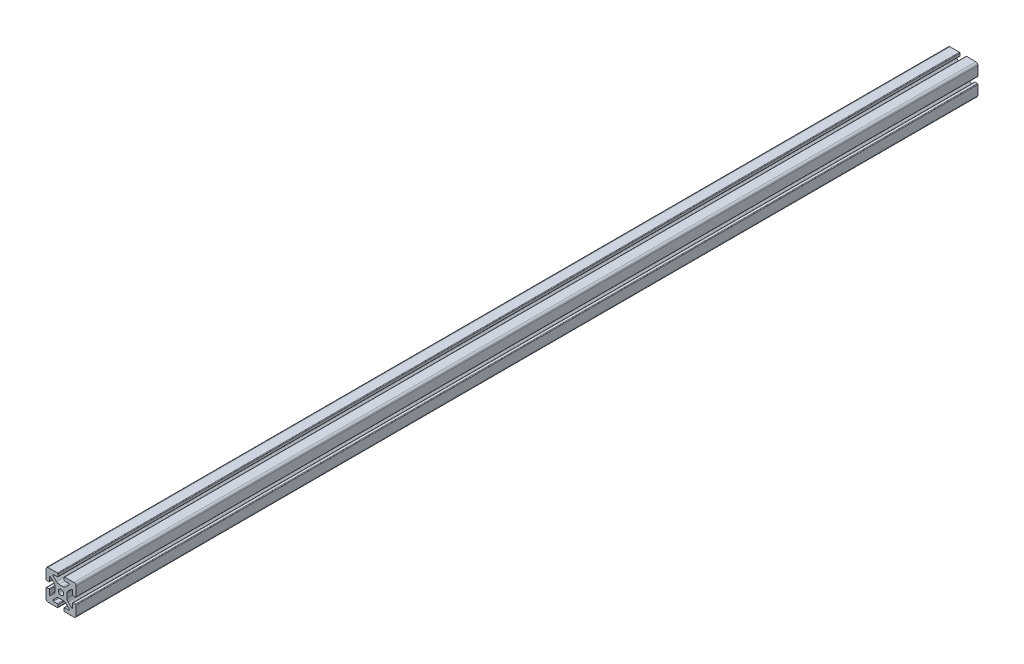
SolidWorks part; units mm, degrees
material "1060 Alloy"
ref_plane "Front Plane" through (0, 0, 0) normal (0, 0, 1) x (1, 0, 0)
ref_plane "Top Plane" through (0, 0, 0) normal (0, 1, 0) x (1, 0, 0)
ref_plane "Right Plane" through (0, 0, 0) normal (1, 0, 0) x (0, 0, -1)
sketch "Sketch1" plane through (0, 0, 0) normal (0, 0, 1) x (1, 0, 0)
  line L72 (4.8, -20) -> (17.2, -20)
  line L73 (20, -17.2) -> (20, -4.8)
  line L74 (19.2, -4) -> (16.1907, -4)
  line L75 (15.3907, -4.8) -> (15.3907, -10.2)
  line L76 (14.025, -10.7657) -> (9.4059, -6.1466)
  line L77 (8, -2.7525) -> (8, 2.7525)
  line L78 (9.4059, 6.1466) -> (14.025, 10.7657)
  line L79 (15.3907, 10.2) -> (15.3907, 4.8)
  line L80 (16.1907, 4) -> (19.2, 4)
  line L81 (20, 4.8) -> (20, 17.2)
  line L82 (17.2, 20) -> (4.8, 20)
  line L83 (4, 19.2) -> (4, 16.1907)
  line L84 (4.8, 15.3907) -> (10.2, 15.3907)
  line L85 (10.7657, 14.025) -> (6.1466, 9.4059)
  line L86 (2.7525, 8) -> (-2.7525, 8)
  line L87 (-6.1466, 9.4059) -> (-10.7657, 14.025)
  line L88 (-10.2, 15.3907) -> (-4.8, 15.3907)
  line L89 (-4, 16.1907) -> (-4, 19.2)
  line L90 (-4.8, 20) -> (-17.2, 20)
  line L91 (-20, 17.2) -> (-20, 4.8)
  line L92 (-19.2, 4) -> (-16.1907, 4)
  line L93 (-15.3907, 4.8) -> (-15.3907, 10.2)
  line L94 (-14.025, 10.7657) -> (-9.4059, 6.1466)
  line L95 (-8, 2.7525) -> (-8, -2.7525)
  line L96 (-9.4059, -6.1466) -> (-14.025, -10.7657)
  line L97 (-15.3907, -10.2) -> (-15.3907, -4.8)
  line L98 (-16.1907, -4) -> (-19.2, -4)
  line L99 (-20, -4.8) -> (-20, -17.2)
  line L100 (-17.2, -20) -> (-4.8, -20)
  line L101 (-4, -19.2) -> (-4, -16.1907)
  line L102 (-4.8, -15.3907) -> (-10.2, -15.3907)
  line L103 (-10.7657, -14.025) -> (-6.1466, -9.4059)
  line L104 (-2.7525, -8) -> (2.7525, -8)
  line L105 (6.1466, -9.4059) -> (10.7657, -14.025)
  line L106 (10.2, -15.3907) -> (4.8, -15.3907)
  line L107 (4, -16.1907) -> (4, -19.2)
  circle A2 centre (0, 0) radius 3.5
  arc A74 (4, -19.2) -> (4.8, -20) centre (4.8, -19.2) ccw
  arc A75 (17.2, -20) -> (20, -17.2) centre (17.2, -17.2) ccw
  arc A76 (20, -4.8) -> (19.2, -4) centre (19.2, -4.8) ccw
  arc A77 (16.1907, -4) -> (15.3907, -4.8) centre (16.1907, -4.8) ccw
  arc A78 (14.025, -10.7657) -> (15.3907, -10.2) centre (14.5907, -10.2) ccw
  arc A79 (8, -2.7525) -> (9.4059, -6.1466) centre (12.8, -2.7525) ccw
  arc A80 (9.4059, 6.1466) -> (8, 2.7525) centre (12.8, 2.7525) ccw
  arc A81 (15.3907, 10.2) -> (14.025, 10.7657) centre (14.5907, 10.2) ccw
  arc A82 (15.3907, 4.8) -> (16.1907, 4) centre (16.1907, 4.8) ccw
  arc A83 (19.2, 4) -> (20, 4.8) centre (19.2, 4.8) ccw
  arc A84 (20, 17.2) -> (17.2, 20) centre (17.2, 17.2) ccw
  arc A85 (4.8, 20) -> (4, 19.2) centre (4.8, 19.2) ccw
  arc A86 (4, 16.1907) -> (4.8, 15.3907) centre (4.8, 16.1907) ccw
  arc A87 (10.7657, 14.025) -> (10.2, 15.3907) centre (10.2, 14.5907) ccw
  arc A88 (2.7525, 8) -> (6.1466, 9.4059) centre (2.7525, 12.8) ccw
  arc A89 (-6.1466, 9.4059) -> (-2.7525, 8) centre (-2.7525, 12.8) ccw
  arc A90 (-10.2, 15.3907) -> (-10.7657, 14.025) centre (-10.2, 14.5907) ccw
  arc A91 (-4.8, 15.3907) -> (-4, 16.1907) centre (-4.8, 16.1907) ccw
  arc A92 (-4, 19.2) -> (-4.8, 20) centre (-4.8, 19.2) ccw
  arc A93 (-17.2, 20) -> (-20, 17.2) centre (-17.2, 17.2) ccw
  arc A94 (-20, 4.8) -> (-19.2, 4) centre (-19.2, 4.8) ccw
  arc A95 (-16.1907, 4) -> (-15.3907, 4.8) centre (-16.1907, 4.8) ccw
  arc A96 (-14.025, 10.7657) -> (-15.3907, 10.2) centre (-14.5907, 10.2) ccw
  arc A97 (-8, 2.7525) -> (-9.4059, 6.1466) centre (-12.8, 2.7525) ccw
  arc A98 (-9.4059, -6.1466) -> (-8, -2.7525) centre (-12.8, -2.7525) ccw
  arc A99 (-15.3907, -10.2) -> (-14.025, -10.7657) centre (-14.5907, -10.2) ccw
  arc A100 (-15.3907, -4.8) -> (-16.1907, -4) centre (-16.1907, -4.8) ccw
  arc A101 (-19.2, -4) -> (-20, -4.8) centre (-19.2, -4.8) ccw
  arc A102 (-20, -17.2) -> (-17.2, -20) centre (-17.2, -17.2) ccw
  arc A103 (-4.8, -20) -> (-4, -19.2) centre (-4.8, -19.2) ccw
  arc A104 (-4, -16.1907) -> (-4.8, -15.3907) centre (-4.8, -16.1907) ccw
  arc A105 (-10.7657, -14.025) -> (-10.2, -15.3907) centre (-10.2, -14.5907) ccw
  arc A106 (-2.7525, -8) -> (-6.1466, -9.4059) centre (-2.7525, -12.8) ccw
  arc A107 (6.1466, -9.4059) -> (2.7525, -8) centre (2.7525, -12.8) ccw
  arc A108 (10.2, -15.3907) -> (10.7657, -14.025) centre (10.2, -14.5907) ccw
  arc A109 (4.8, -15.3907) -> (4, -16.1907) centre (4.8, -16.1907) ccw
extrude "Boss-Extrude1" add sketch "Sketch1" along normal mid plane 1200
